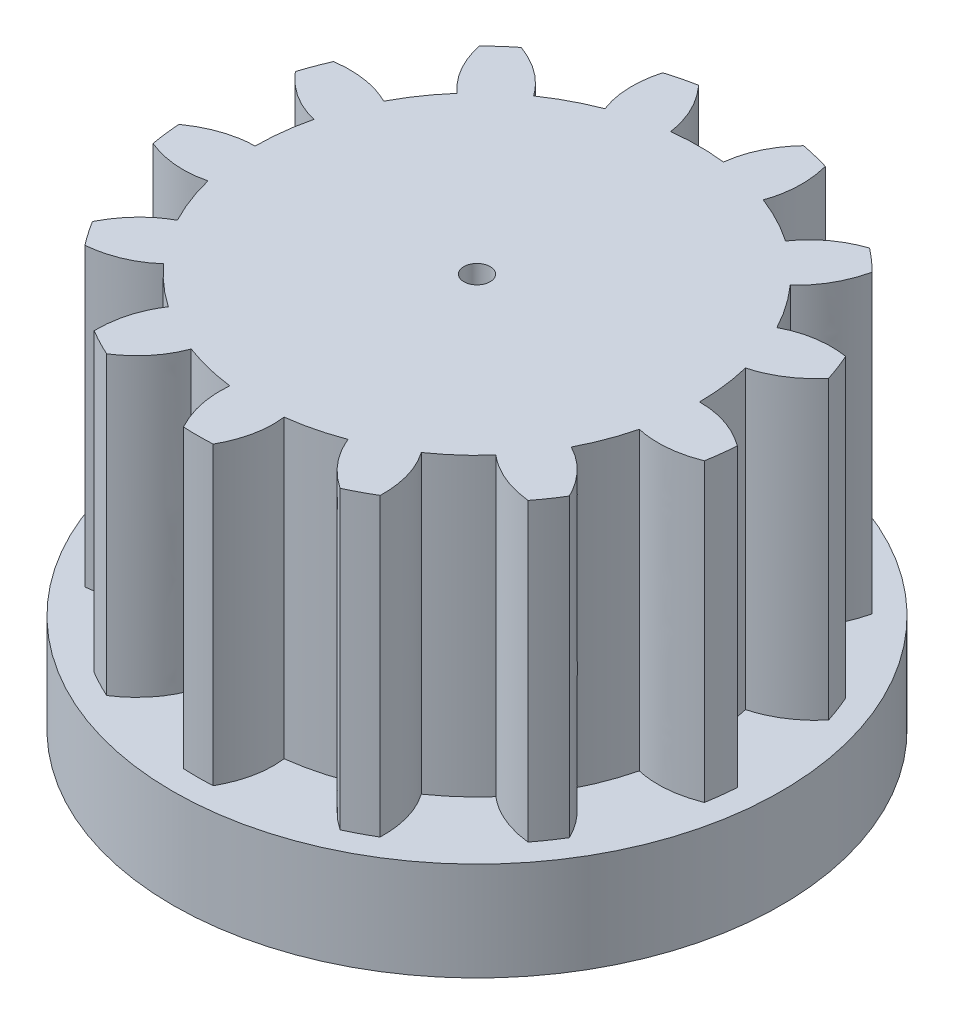
SolidWorks part; units mm, degrees
ref_plane "Front Plane" through (0, 0, 0) normal (0, 0, 1) x (1, 0, 0)
ref_plane "Top Plane" through (0, 0, 0) normal (0, 1, 0) x (1, 0, 0)
ref_plane "Right Plane" through (0, 0, 0) normal (1, 0, 0) x (0, 0, -1)
sketch "Sketch1" plane through (0, 0, 0) normal (0, 1, 0) x (1, 0, 0)
  line L0 (0, 0) -> (0, 17.0926) construction
  line L1 (0, 0) -> (3.5061, 14.2208) construction
  line L2 (0, 0) -> (1.9234, 15.8361) construction
  line L3 (0, 0) -> (4.6786, 12.3295) construction
  circle A3 centre (0, 0) radius 0.4
  arc A4 (-5.0652, 4.4616) -> (-5.9762, 3.138) centre (0, 0) ccw
  arc A6 (-2.4116, 6.3045) -> (-3.8334, 5.5559) centre (0, 0) ccw
  arc A7 (0.8138, 6.7008) -> (-0.8124, 6.7009) centre (0, 0) ccw
  arc A8 (3.8185, 5.5661) -> (2.3948, 6.3109) centre (0, 0) ccw
  arc A9 (5.9678, 3.154) -> (5.0533, 4.4751) centre (0, 0) ccw
  arc A10 (6.75, 0.0193) -> (6.5542, 1.6141) centre (0, 0) ccw
  arc A11 (5.9858, -3.1198) -> (6.5536, -1.6166) centre (0, 0) ccw
  arc A12 (3.8503, -5.5442) -> (5.0516, -4.477) centre (0, 0) ccw
  arc A13 (0.8328, -6.6984) -> (2.3924, -6.3118) centre (0, 0) ccw
  arc A14 (-2.3755, -6.3182) -> (-0.8149, -6.7006) centre (0, 0) ccw
  arc A15 (-5.0396, -4.4905) -> (-3.8355, -5.5544) centre (0, 0) ccw
  arc A16 (-6.5492, -1.6341) -> (-5.9774, -3.1358) centre (0, 0) ccw
  arc A17 (-6.5585, 1.5966) -> (-6.75, 0.0013) centre (0, 0) ccw
  arc A18 (-7.781, 3.4215) -> (-8.1003, 2.5759) centre (0, 0) ccw
  arc A19 (-8.4797, -0.5864) -> (-8.3695, -1.4836) centre (0, 0) ccw
  arc A20 (-7.2359, -4.46) -> (-6.7214, -5.2032) centre (0, 0) ccw
  arc A21 (-4.3344, -7.3118) -> (-3.5335, -7.7308) centre (0, 0) ccw
  arc A22 (-5.2996, 6.6456) -> (-5.9754, 6.0452) centre (0, 0) ccw
  arc A23 (-1.6043, 8.3472) -> (-2.4816, 8.1297) centre (0, 0) ccw
  arc A24 (8.3737, -1.46) -> (8.4814, -0.5625) centre (0, 0) ccw
  arc A25 (8.093, 2.5987) -> (7.7713, 3.4434) centre (0, 0) ccw
  arc A28 (2.4587, 8.1366) -> (1.5807, 8.3517) centre (0, 0) ccw
  arc A31 (5.9583, 6.062) -> (5.2809, 6.6605) centre (0, 0) ccw
  arc A32 (6.736, -5.1842) -> (7.2485, -4.4396) centre (0, 0) ccw
  arc A33 (3.5553, -7.7208) -> (4.355, -7.2996) centre (0, 0) ccw
  arc A34 (-0.44, -8.4886) -> (0.4639, -8.4873) centre (0, 0) ccw
  spline S0 degree 3 poles (0.633, 5.2117) (0.7252, 5.9828) (1.0144, 6.8191) (1.6201, 7.3229) knots 0 0 0 0 1 1 1 1 construction
  spline S1 degree 1 poles (1.6201, 7.3229) (1.9696, 7.2368) knots 0 0 1 1 construction
  spline S2 degree 3 poles (1.8622, 4.9086) (2.139, 5.6342) (2.2717, 6.5091) (1.9696, 7.2368) knots 0 0 0 0 1 1 1 1 construction
  spline S3 degree 3 poles (3.93, 3.481) (4.5123, 3.9948) (5.0364, 4.7079) (5.1071, 5.4925) knots 0 0 0 0 1 1 1 1 construction
  spline S4 degree 3 poles (2.9825, 4.3206) (3.4225, 4.9605) (4.0672, 5.5666) (4.8376, 5.7313) knots 0 0 0 0 1 1 1 1 construction
  spline S5 degree 1 poles (4.8376, 5.7313) (5.1071, 5.4925) knots 0 0 1 1 construction
  spline S6 degree 3 poles (5.0976, 1.2559) (5.852, 1.4403) (6.6474, 1.8281) (7.0746, 2.49) knots 0 0 0 0 1 1 1 1 construction
  spline S7 degree 3 poles (4.6487, 2.4397) (5.3357, 2.8018) (6.1883, 3.0389) (6.947, 2.8266) knots 0 0 0 0 1 1 1 1 construction
  spline S8 degree 1 poles (6.947, 2.8266) (7.0746, 2.49) knots 0 0 1 1 construction
  spline S9 degree 3 poles (5.0973, -1.2569) (5.851, -1.4442) (6.7355, -1.4705) (7.4214, -1.083) knots 0 0 0 0 1 1 1 1 construction
  spline S10 degree 3 poles (5.25, -0.0002) (6.0266, 0.0012) (6.8917, -0.1851) (7.4648, -0.7256) knots 0 0 0 0 1 1 1 1 construction
  spline S11 degree 1 poles (7.4648, -0.7256) (7.4214, -1.083) knots 0 0 1 1 construction
  spline S12 degree 3 poles (3.9293, -3.4818) (4.5096, -3.9979) (5.2806, -4.4322) (6.068, -4.4078) knots 0 0 0 0 1 1 1 1 construction
  spline S13 degree 3 poles (4.6486, -2.4399) (5.3369, -2.7996) (6.0163, -3.3666) (6.2726, -4.1115) knots 0 0 0 0 1 1 1 1 construction
  spline S14 degree 1 poles (6.2726, -4.1115) (6.068, -4.4078) knots 0 0 1 1 construction
  spline S15 degree 3 poles (1.8612, -4.909) (2.1351, -5.6357) (2.616, -6.3786) (3.3246, -6.7229) knots 0 0 0 0 1 1 1 1 construction
  spline S16 degree 3 poles (2.9822, -4.3208) (3.4245, -4.9591) (3.7626, -5.7769) (3.6434, -6.5556) knots 0 0 0 0 1 1 1 1 construction
  spline S17 degree 1 poles (3.6434, -6.5556) (3.3246, -6.7229) knots 0 0 1 1 construction
  spline S18 degree 3 poles (-0.6334, -5.2117) (-0.7285, -5.9824) (-0.6479, -6.8636) (-0.1805, -7.4978) knots 0 0 0 0 1 1 1 1 construction
  spline S19 degree 3 poles (0.6327, -5.2117) (0.7277, -5.9825) (0.647, -6.8637) (0.1795, -7.4979) knots 0 0 0 0 1 1 1 1 construction
  spline S20 degree 1 poles (0.1795, -7.4979) (-0.1805, -7.4978) knots 0 0 1 1 construction
  spline S21 degree 3 poles (-2.9828, -4.3204) (-3.4252, -4.9586) (-3.7634, -5.7764) (-3.6443, -6.5551) knots 0 0 0 0 1 1 1 1 construction
  spline S22 degree 3 poles (-1.8618, -4.9088) (-2.1359, -5.6354) (-2.6168, -6.3782) (-3.3255, -6.7224) knots 0 0 0 0 1 1 1 1 construction
  spline S23 degree 1 poles (-3.3255, -6.7224) (-3.6443, -6.5551) knots 0 0 1 1 construction
  spline S24 degree 3 poles (-4.6489, -2.4393) (-5.3372, -2.7989) (-6.0167, -3.3658) (-6.2731, -4.1107) knots 0 0 0 0 1 1 1 1 construction
  spline S25 degree 3 poles (-3.9298, -3.4813) (-4.5101, -3.9973) (-5.2812, -4.4315) (-6.0686, -4.407) knots 0 0 0 0 1 1 1 1 construction
  spline S26 degree 1 poles (-6.0686, -4.407) (-6.2731, -4.1107) knots 0 0 1 1 construction
  spline S27 degree 3 poles (-5.25, 0.0006) (-6.0266, 0.0021) (-6.8917, -0.1841) (-7.4649, -0.7246) knots 0 0 0 0 1 1 1 1 construction
  spline S28 degree 3 poles (-5.0975, -1.2563) (-5.8512, -1.4435) (-6.7357, -1.4696) (-7.4215, -1.082) knots 0 0 0 0 1 1 1 1 construction
  spline S29 degree 1 poles (-7.4215, -1.082) (-7.4649, -0.7246) knots 0 0 1 1 construction
  spline S30 degree 3 poles (-4.6484, 2.4403) (-5.3353, 2.8025) (-6.1879, 3.0397) (-6.9466, 2.8276) knots 0 0 0 0 1 1 1 1 construction
  spline S31 degree 3 poles (-5.0974, 1.2566) (-5.8518, 1.441) (-6.6471, 1.829) (-7.0743, 2.4909) knots 0 0 0 0 1 1 1 1 construction
  spline S32 degree 1 poles (-7.0743, 2.4909) (-6.9466, 2.8276) knots 0 0 1 1 construction
  spline S33 degree 3 poles (-2.9819, 4.321) (-3.4218, 4.9609) (-4.0665, 5.5672) (-4.8369, 5.7319) knots 0 0 0 0 1 1 1 1 construction
  spline S34 degree 3 poles (-3.9296, 3.4815) (-4.5118, 3.9954) (-5.0358, 4.7085) (-5.1064, 5.4932) knots 0 0 0 0 1 1 1 1 construction
  spline S35 degree 1 poles (-5.1064, 5.4932) (-4.8369, 5.7319) knots 0 0 1 1 construction
  spline S36 degree 3 poles (-0.6323, 5.2118) (-0.7244, 5.9829) (-1.0135, 6.8193) (-1.6191, 7.3232) knots 0 0 0 0 1 1 1 1 construction
  spline S37 degree 3 poles (-1.8615, 4.9089) (-2.1382, 5.6345) (-2.2708, 6.5094) (-1.9686, 7.237) knots 0 0 0 0 1 1 1 1 construction
  spline S38 degree 1 poles (-1.9686, 7.237) (-1.6191, 7.3232) knots 0 0 1 1 construction
  spline S39 degree 3 poles (-4.6484, 2.4403) (-4.4519, 2.8146) (-4.2099, 3.1651) (-3.9296, 3.4815) knots 0 0 0 0 0.038449 0.038449 0.038449 0.038449 construction
  spline S40 degree 3 poles (-2.9819, 4.321) (-2.6339, 4.5611) (-2.2568, 4.759) (-1.8615, 4.9089) knots 0.076923 0.076923 0.076923 0.076923 0.115372 0.115372 0.115372 0.115372 construction
  spline S41 degree 3 poles (-0.6323, 5.2118) (-0.2126, 5.2627) (0.2133, 5.2627) (0.633, 5.2117) (0.633, 5.2117) knots 0.153846 0.153846 0.153846 0.153846 0.192296 0.192296 0.192296 0.192296 0.192296 construction
  spline S42 degree 3 poles (-5.25, 0.0006) (-5.25, 0.4233) (-5.1986, 0.8461) (-5.0974, 1.2566) knots 0.923077 0.923077 0.923077 0.923077 0.961526 0.961526 0.961526 0.961526 construction
  spline S43 degree 3 poles (-4.6489, -2.4393) (-4.8453, -2.0649) (-4.9963, -1.6667) (-5.0975, -1.2563) knots 0.846154 0.846154 0.846154 0.846154 0.884603 0.884603 0.884603 0.884603 construction
  spline S44 degree 3 poles (-2.9828, -4.3204) (-3.3307, -4.0802) (-3.6494, -3.7977) (-3.9298, -3.4813) knots 0.769231 0.769231 0.769231 0.769231 0.80768 0.80768 0.80768 0.80768 construction
  spline S45 degree 3 poles (-0.6334, -5.2117) (-1.053, -5.1607) (-1.4665, -5.0587) (-1.8618, -4.9088) knots 0.692308 0.692308 0.692308 0.692308 0.730757 0.730757 0.730757 0.730757 construction
  spline S46 degree 3 poles (1.8612, -4.909) (1.4659, -5.0589) (1.0524, -5.1608) (0.6327, -5.2117) knots 0.615385 0.615385 0.615385 0.615385 0.653834 0.653834 0.653834 0.653834 construction
  spline S47 degree 3 poles (3.9293, -3.4818) (3.6489, -3.7982) (3.3302, -4.0806) (2.9822, -4.3208) knots 0.538462 0.538462 0.538462 0.538462 0.576911 0.576911 0.576911 0.576911 construction
  spline S48 degree 3 poles (5.0973, -1.2569) (4.9961, -1.6674) (4.8451, -2.0656) (4.6486, -2.4399) knots 0.461538 0.461538 0.461538 0.461538 0.499988 0.499988 0.499988 0.499988 construction
  spline S49 degree 3 poles (5.0976, 1.2559) (5.1987, 0.8454) (5.25, 0.4226) (5.25, -0.0002) knots 0.384615 0.384615 0.384615 0.384615 0.423065 0.423065 0.423065 0.423065 construction
  spline S50 degree 3 poles (3.93, 3.481) (4.2104, 3.1645) (4.4523, 2.814) (4.6487, 2.4397) knots 0.307692 0.307692 0.307692 0.307692 0.346142 0.346142 0.346142 0.346142 construction
  spline S51 degree 3 poles (1.8622, 4.9086) (2.2575, 4.7587) (2.6345, 4.5607) (2.9825, 4.3206) knots 0.230769 0.230769 0.230769 0.230769 0.269219 0.269219 0.269219 0.269219 construction
  spline S52 degree 3 poles (0.7945, 6.7031) (0.8653, 7.3126) (1.1274, 7.8622) (1.5807, 8.3517) knots 0 0 0 0 0.872429 0.872429 0.872429 0.872429
  spline S53 degree 3 poles (2.4587, 8.1366) (2.623, 7.4967) (2.6017, 6.8881) (2.3948, 6.3109) knots 0.127683 0.127683 0.127683 0.127683 1 1 1 1
  spline S54 degree 3 poles (3.8185, 5.5661) (4.1646, 6.0729) (4.652, 6.4377) (5.2809, 6.6605) knots 0 0 0 0 0.872429 0.872429 0.872429 0.872429
  spline S55 degree 3 poles (5.9583, 6.062) (5.8065, 5.419) (5.5048, 4.89) (5.0533, 4.4751) knots 0.127683 0.127683 0.127683 0.127683 1 1 1 1
  spline S56 degree 3 poles (5.9678, 3.154) (6.5097, 3.4419) (7.1109, 3.5384) (7.7713, 3.4434) knots 0 0 0 0 0.872429 0.872429 0.872429 0.872429
  spline S57 degree 3 poles (8.093, 2.5987) (7.6597, 2.0999) (7.1468, 1.7717) (6.5542, 1.6141) knots 0.127683 0.127683 0.127683 0.127683 1 1 1 1
  spline S58 degree 3 poles (6.75, 0.0193) (7.3636, 0.0224) (7.9407, -0.1715) (8.4814, -0.5625) knots 0 0 0 0 0.872429 0.872429 0.872429 0.872429
  spline S59 degree 3 poles (8.3737, -1.46) (7.7582, -1.7003) (7.1515, -1.7525) (6.5536, -1.6166) knots 0.127683 0.127683 0.127683 0.127683 1 1 1 1
  spline S60 degree 3 poles (5.9858, -3.1198) (6.5306, -3.4022) (6.9515, -3.8421) (7.2485, -4.4396) knots 0 0 0 0 0.872429 0.872429 0.872429 0.872429
  spline S61 degree 3 poles (6.736, -5.1842) (6.0794, -5.1109) (5.5179, -4.8752) (5.0516, -4.477) knots 0.127683 0.127683 0.127683 0.127683 1 1 1 1
  spline S62 degree 3 poles (3.8503, -5.5442) (4.2015, -6.0474) (4.3697, -6.6325) (4.355, -7.2996) knots 0 0 0 0 0.872429 0.872429 0.872429 0.872429
  spline S63 degree 3 poles (3.5553, -7.7208) (3.0079, -7.3508) (2.6202, -6.8811) (2.3924, -6.3118) knots 0.127683 0.127683 0.127683 0.127683 1 1 1 1
  spline S64 degree 3 poles (0.8328, -6.6984) (0.9098, -7.3072) (0.7869, -7.9035) (0.4639, -8.4873) knots 0 0 0 0 0.872429 0.872429 0.872429 0.872429
  spline S65 degree 3 poles (-0.44, -8.4886) (-0.7527, -7.9066) (-0.8777, -7.3106) (-0.8149, -6.7006) knots 0.127683 0.127683 0.127683 0.127683 1 1 1 1
  spline S66 degree 3 poles (-2.3755, -6.3182) (-2.5902, -6.8931) (-2.9762, -7.3639) (-3.5335, -7.7308) knots 0 0 0 0 0.872429 0.872429 0.872429 0.872429
  spline S67 degree 3 poles (-4.3344, -7.3118) (-4.3409, -6.6511) (-4.1746, -6.0653) (-3.8355, -5.5544) knots 0.127683 0.127683 0.127683 0.127683 1 1 1 1
  spline S68 degree 3 poles (-5.0396, -4.4905) (-5.4969, -4.8998) (-6.0575, -5.1373) (-6.7214, -5.2032) knots 0 0 0 0 0.872429 0.872429 0.872429 0.872429
  spline S69 degree 3 poles (-7.2359, -4.46) (-6.9346, -3.872) (-6.5151, -3.4306) (-5.9774, -3.1358) knots 0.127683 0.127683 0.127683 0.127683 1 1 1 1
  spline S70 degree 3 poles (-6.5492, -1.6341) (-7.1443, -1.784) (-7.751, -1.7338) (-8.3695, -1.4836) knots 0 0 0 0 0.872429 0.872429 0.872429 0.872429
  spline S71 degree 3 poles (-8.4797, -0.5864) (-7.9397, -0.2058) (-7.3631, -0.0099) (-6.75, 0.0013) knots 0.127683 0.127683 0.127683 0.127683 1 1 1 1
  spline S72 degree 3 poles (-6.5585, 1.5966) (-7.155, 1.7405) (-7.669, 2.0669) (-8.1003, 2.5759) knots 0 0 0 0 0.872429 0.872429 0.872429 0.872429
  spline S73 degree 3 poles (-7.781, 3.4215) (-7.1259, 3.5075) (-6.5243, 3.413) (-5.9762, 3.138) knots 0.127683 0.127683 0.127683 0.127683 1 1 1 1
  spline S74 degree 3 poles (-5.0652, 4.4616) (-5.5266, 4.8662) (-5.83, 5.3941) (-5.9754, 6.0452) knots 0 0 0 0 0.872429 0.872429 0.872429 0.872429
  spline S75 degree 3 poles (-5.2996, 6.6456) (-4.6796, 6.4173) (-4.1909, 6.0541) (-3.8334, 5.5559) knots 0.127683 0.127683 0.127683 0.127683 1 1 1 1
  spline S76 degree 3 poles (-2.4116, 6.3045) (-2.6321, 6.8771) (-2.6555, 7.4855) (-2.4816, 8.1297) knots 0 0 0 0 0.872429 0.872429 0.872429 0.872429
  spline S77 degree 3 poles (-1.6043, 8.3472) (-1.1613, 7.857) (-0.8973, 7.3082) (-0.8124, 6.7009) knots 0.127683 0.127683 0.127683 0.127683 1 1 1 1
  point P62 (1.792, 8.5633)
  point P64 (0, 0)
  point P66 (2.3745, 8.4197)
  point P121 (0, 0)
  dimension "D2" = 13.5
  dimension "D3" = 0.31
  dimension "D4" = 0.8
  dimension "D9" = 17
  dimension "D5" = 13.85
  dimension "D6" = 6.925
  dimension "D7" = 6.93
  dimension "D8" = 0.6
extrude "Boss-Extrude1" add sketch "Sketch1" along normal blind 9
sketch "Sketch2" plane through (0, 0, 0) normal (0, -1, 0) x (1, 0, 0)
  circle A1 centre (0, 0) radius 9.25
  dimension "D1" = 18.5
extrude "Boss-Extrude2" add sketch "Sketch2" along normal blind 3
sketch "Croquis1" plane through (0, -3, 0) normal (0, -1, 0) x (1, 0, 0)
  circle A0 centre (0, 0) radius 2.3
  dimension "D1" = 4.6
extrude "Cortar-Extruir1" cut sketch "Croquis1" against normal blind 2
